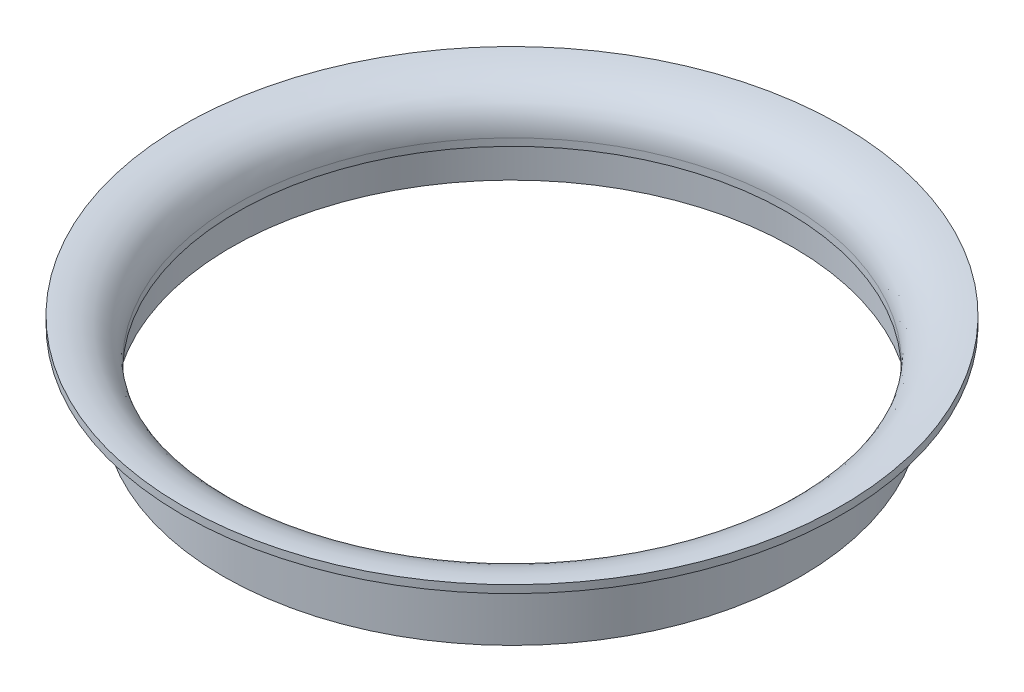
SolidWorks part; units mm, degrees
material "Настроенная пользователем пластмасса"
ref_plane "Спереди" through (0, 0, 0) normal (0, 0, 1) x (1, 0, 0)
ref_plane "Сверху" through (0, 0, 0) normal (0, 1, 0) x (1, 0, 0)
ref_plane "Справа" through (0, 0, 0) normal (1, 0, 0) x (0, 0, -1)
sketch "Эскиз1" plane through (0, 0, 0) normal (0, 0, 1) x (1, 0, 0)
  line L0 (0, 0) -> (36.25, 0)
  line L1 (36.25, 0) -> (37.25, 0)
  line L2 (37.25, 0) -> (37.25, 6)
  line L5 (42.5, 9.5) -> (42.5, 10.5)
  line L8 (35.5, 4.3) -> (36.25, 4.3)
  line L9 (36.25, 4.3) -> (36.25, 0)
  line L10 (37.25, 7.4) -> (37.25, 2.3522) construction
  line L11 (45.306, 9.5) -> (39.694, 9.5) construction
  line L12 (45.4759, 10.5) -> (39.5241, 10.5) construction
  line L13 (35.5, 9.5574) -> (35.5, 5.4485) construction
  line L14 (35.5, 5.2463) -> (35.5, 4.3)
  line L15 (0, 0) -> (0, 7.7543) construction
  spline S0 degree 3 poles (37.25, 6) (37.25, 8.1032) (38.9924, 9.5) (42.5, 9.5) knots 0 0 0 0 1 1 1 1
  spline S1 degree 3 poles (35.5, 5.2463) (35.5, 8.1434) (37.3082, 10.5) (42.5, 10.5) knots 0 0 0 0 1 1 1 1
  dimension "D2" = 36.25
  dimension "D3" = 1
  dimension "D4" = 6
  dimension "D7" = 4.3
revolve "Повернуть1" add sketch "Эскиз1" angle 360 about L15
